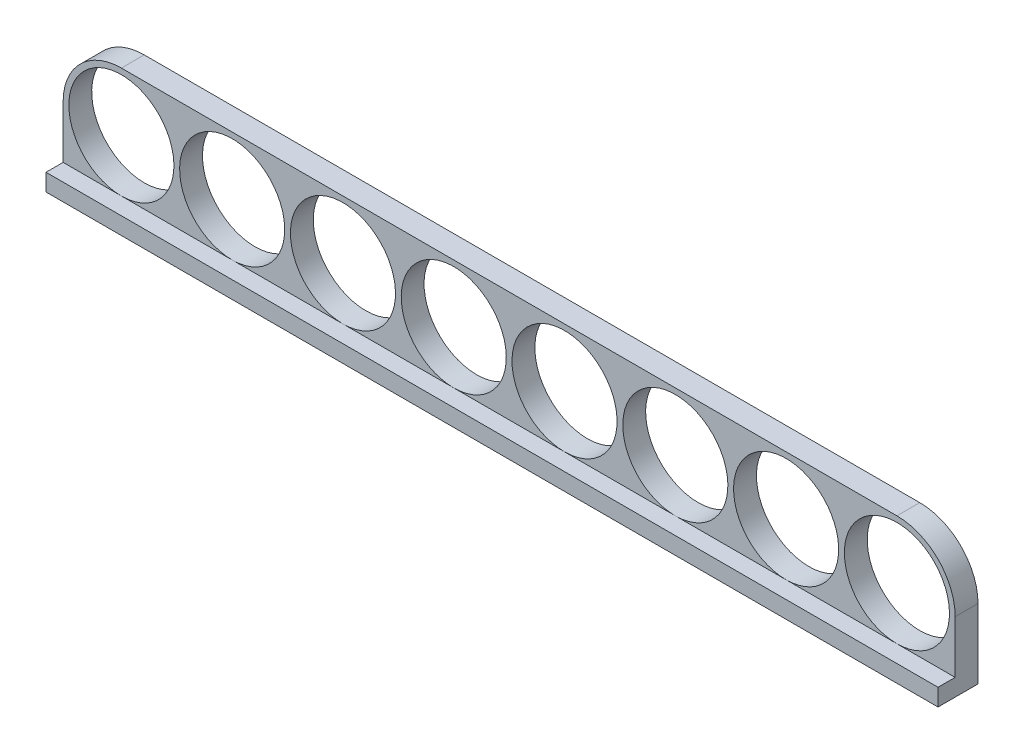
SolidWorks part; units mm, degrees
ref_plane "Front Plane" through (0, 0, 0) normal (0, 0, 1) x (1, 0, 0)
ref_plane "Top Plane" through (0, 0, 0) normal (0, 1, 0) x (1, 0, 0)
ref_plane "Right Plane" through (0, 0, 0) normal (1, 0, 0) x (0, 0, -1)
sketch "Sketch1" plane through (0, 0, 0) normal (0, 0, 1) x (1, 0, 0)
  line L0 (0, 10.2) -> (135.8, 10.2)
  line L1 (0, -9.2) -> (135.8, -9.2) construction
  line L2 (0, 0) -> (135.8, 0) construction
  line L3 (-10.2, 0) -> (-10.2, -12.2)
  line L4 (-10.2, -12.2) -> (146, -12.2)
  line L5 (146, -12.2) -> (146, 0)
  circle A0 centre (0, 0) radius 9.2
  circle A1 centre (19.4, 0) radius 9.2
  circle A2 centre (38.8, 0) radius 9.2
  circle A3 centre (58.2, 0) radius 9.2
  circle A4 centre (77.6, 0) radius 9.2
  circle A5 centre (97, 0) radius 9.2
  circle A6 centre (116.4, 0) radius 9.2
  circle A7 centre (135.8, 0) radius 9.2
  arc A8 (135.8, 10.2) -> (146, 0) centre (135.8, 0) cw
  arc A9 (0, 10.2) -> (-10.2, 0) centre (0, 0) ccw
  point P4 (9.2, 0)
  point P18 (10.2, 0)
  dimension "D1" = 18.4
  dimension "D3" = 10.2
  dimension "D4" = 3
  dimension "D2" = 8
extrude "Boss-Extrude1" add sketch "Sketch1" along normal blind 4
sketch "Sketch2" plane through (0, 0, 4) normal (0, 0, 1) x (1, 0, 0)
  line L0 (146, -12.2) -> (146, 0) construction
  line L1 (-10.2, -12.2) -> (146, -12.2)
  line L2 (-10.2, -12.2) -> (-10.2, -9.2)
  line L3 (-10.2, -9.2) -> (146, -9.2)
  line L4 (146, -12.2) -> (146, -9.2)
  dimension "D1" = 3
extrude "Boss-Extrude2" add sketch "Sketch2" along normal blind 3
